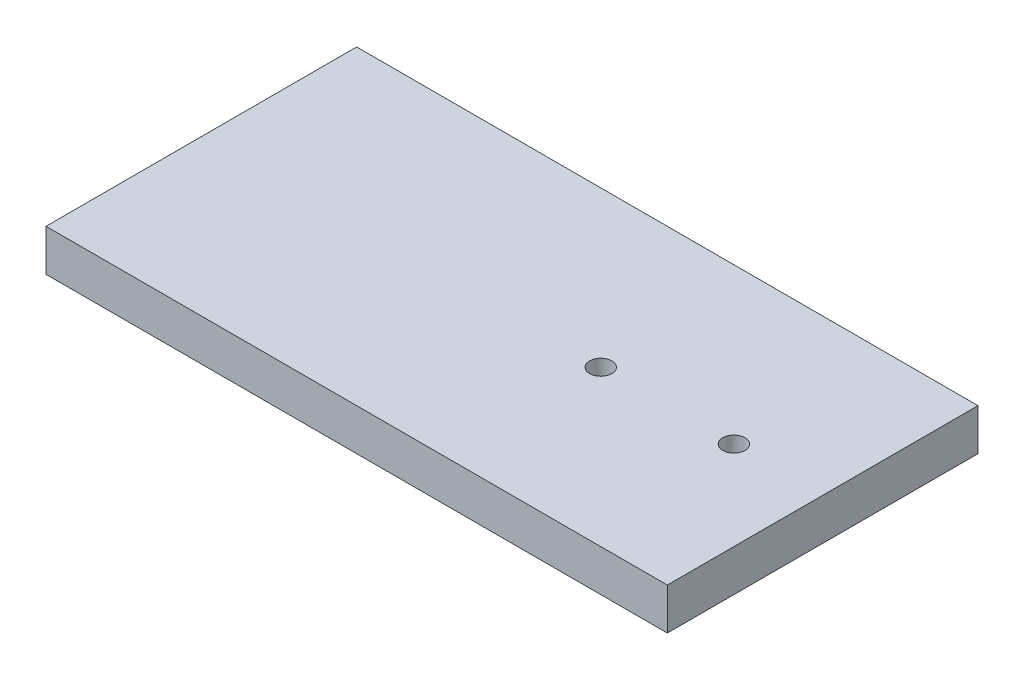
SolidWorks part; units mm, degrees
ref_plane "Front" through (0, 0, 0) normal (0, 0, 1) x (1, 0, 0)
ref_plane "Top" through (0, 0, 0) normal (0, 1, 0) x (1, 0, 0)
ref_plane "Right" through (0, 0, 0) normal (1, 0, 0) x (0, 0, -1)
sketch "Sketch1" plane through (0, 0, 0) normal (0, 1, 0) x (1, 0, 0)
  line L1 (88.9, 44.45) -> (-88.9, 44.45)
  line L2 (88.9, 44.45) -> (88.9, -44.45)
  line L3 (88.9, -44.45) -> (-88.9, -44.45)
  line L4 (-88.9, 44.45) -> (-88.9, -44.45)
  line L5 (88.9, 44.45) -> (-88.9, -44.45) construction
  line L6 (88.9, -44.45) -> (-88.9, 44.45) construction
  point P0 (0, 0)
  dimension "D1" = 177.8
  dimension "D2" = 88.9
extrude "Boss-Extrude1" add sketch "Sketch1" along normal blind 11.9062
hole_wizard "1/4 (0.25) Diameter Hole1" positions "Sketch2" profile "Sketch3" hole size "1/4" standard "ANSI Inch" end condition through all
sketch "Sketch2" plane through (0, 0, 0) normal (0, -1, 0) x (-1, 0, 0)
  line L0 (-88.9, -44.45) -> (-88.9, 44.45) construction
  point P0 (-63.5, 0)
  point P3 (-25.4, 0)
  point P9 (-88.9, 0)
  dimension "D1" = 25.4
  dimension "D2" = 63.5
sketch "Sketch3" plane through (63.5, 0, 0) normal (1, 0, 0) x (0, 0, -1)
  line L0 (0, 0) -> (0, 11.9062)
  line L1 (0, 11.9062) -> (3.175, 11.9062)
  line L2 (3.175, 11.9062) -> (3.175, 0)
  line L5 (3.175, 0) -> (0, 0)
  line L11 (0, -6.35) -> (0, 107.95) construction
  dimension "Thru Hole Dia." = 6.35
  dimension "Thru Hole Depth" = 11.9062
